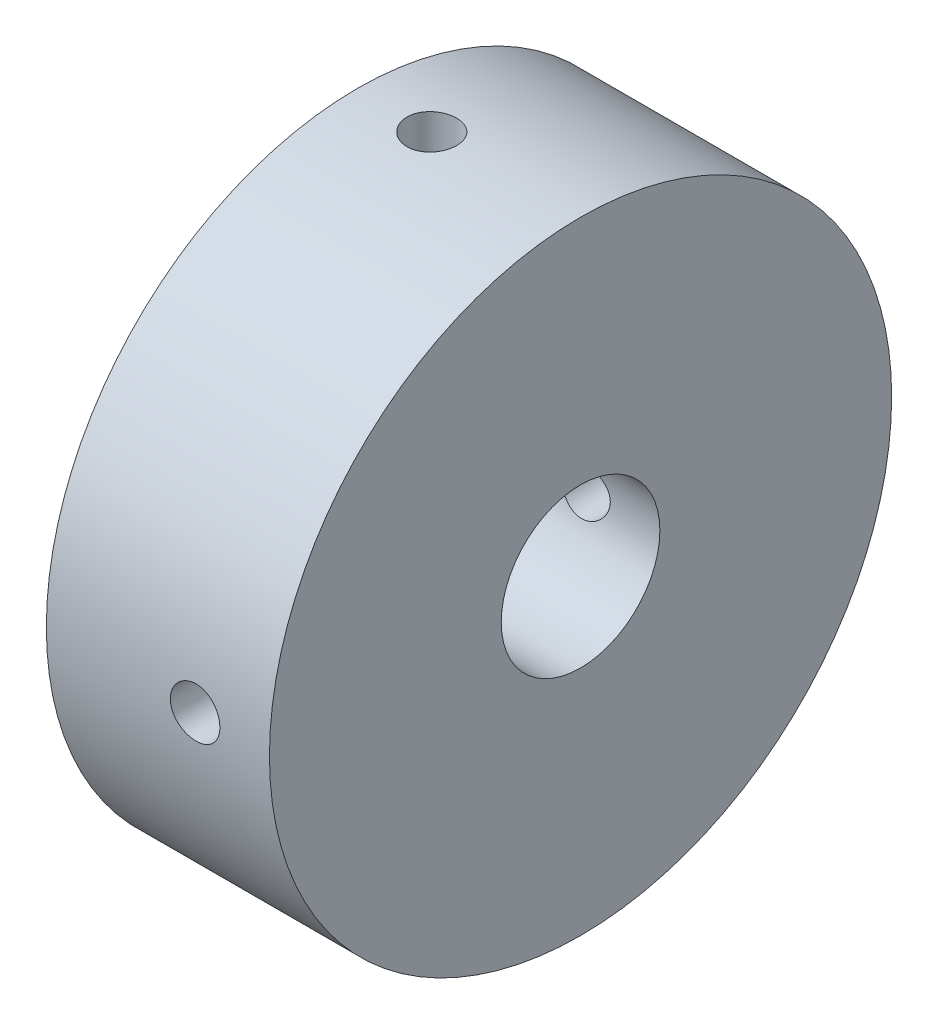
SolidWorks part; units mm, degrees
ref_plane "前视基准面" through (0, 0, 0) normal (0, 0, 1) x (1, 0, 0)
ref_plane "上视基准面" through (0, 0, 0) normal (0, 1, 0) x (1, 0, 0)
ref_plane "右视基准面" through (0, 0, 0) normal (1, 0, 0) x (0, 0, -1)
other "Configuration Table"
sketch "草图1" plane through (0, 0, 0) normal (1, 0, 0) x (0, 0, -1)
  circle A0 centre (0, 0) radius 12.55
  dimension "D1" = 25.1
extrude "凸台-拉伸1" add sketch "草图1" along normal blind 9
sketch "草图2" plane through (0, 0, 0) normal (-1, 0, 0) x (0, 0, 1)
  circle A0 centre (0, 0) radius 3.2
  dimension "D1" = 6.4
extrude "切除-拉伸1" cut sketch "草图2" against normal up to next
sketch "草图3" plane through (0, 0, 0) normal (0, 1, 0) x (1, 0, 0)
  line L0 (0, 12.55) -> (0, -12.55) construction
  circle A0 centre (3, 0) radius 1
  dimension "D1" = 2
  dimension "D2" = 3
extrude "切除-拉伸2" cut sketch "草图3" against normal up to next and the other way up to next
sketch "草图4" plane through (0, 0, 0) normal (0, 0, 1) x (1, 0, 0)
  line L0 (9, -12.55) -> (9, 12.55) construction
  circle A0 centre (6, 0) radius 1
  dimension "D2" = 2
  dimension "D1" = 3
extrude "切除-拉伸3" cut sketch "草图4" against normal blind 19 and the other way blind 21
